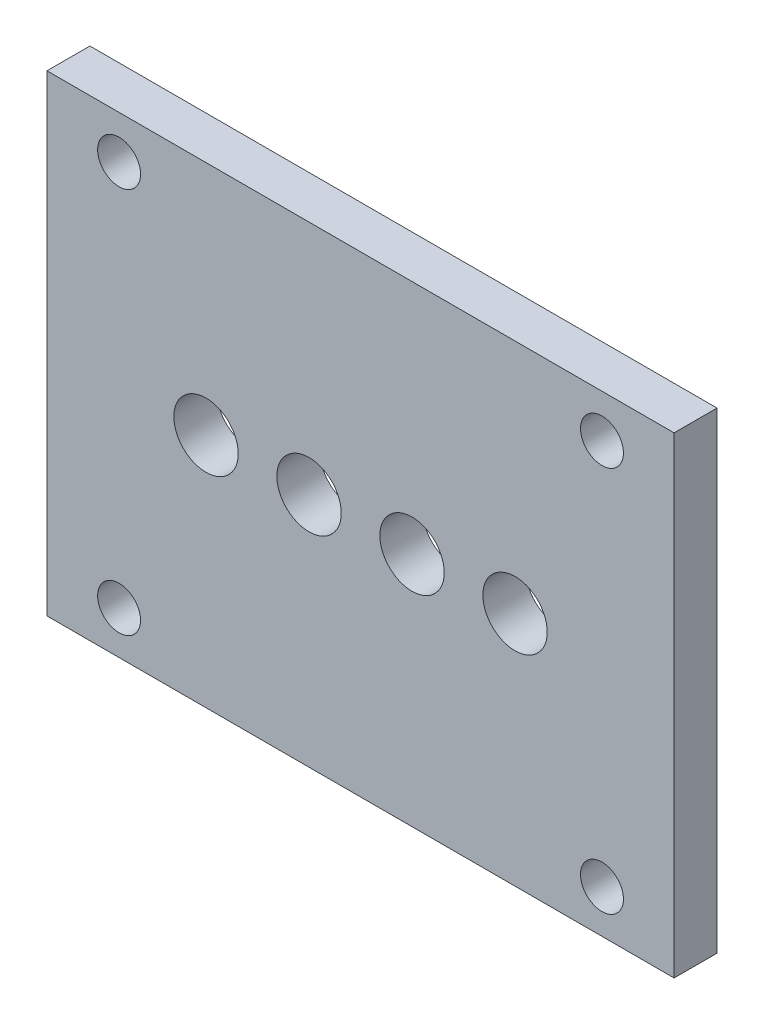
SolidWorks part; units mm, degrees
ref_plane "Front Plane" through (0, 0, 0) normal (0, 0, 1) x (1, 0, 0)
ref_plane "Top Plane" through (0, 0, 0) normal (0, 1, 0) x (1, 0, 0)
ref_plane "Right Plane" through (0, 0, 0) normal (1, 0, 0) x (0, 0, -1)
sketch "Sketch1" plane through (0, 0, 0) normal (0, 0, 1) x (1, 0, 0)
  line L1 (-92.7735, 69.85) -> (92.7735, 69.85)
  line L2 (-92.7735, 69.85) -> (-92.7735, -69.85)
  line L3 (-92.7735, -69.85) -> (92.7735, -69.85)
  line L4 (92.7735, 69.85) -> (92.7735, -69.85)
  dimension "D1" = 139.7
  dimension "D2" = 185.547
  dimension "D3" = 69.85
  dimension "D4" = 92.7735
extrude "Boss-Extrude1" add sketch "Sketch1" along normal blind 12.7
sketch "Sketch2" plane through (0, 0, 12.7) normal (0, 0, 1) x (1, 0, 0)
  line L0 (-45.72, 0) -> (45.72, 0) construction
  circle A0 centre (-45.72, 0) radius 9.525
  circle A1 centre (-15.24, 0) radius 9.525
  circle A2 centre (15.24, 0) radius 9.525
  circle A3 centre (45.72, 0) radius 9.525
  point P3 (0, 0)
  point P9 (0, 0)
  dimension "D2" = 19.05
  dimension "D1" = 4
extrude "Cut-Extrude1" cut sketch "Sketch2" against normal through all
sketch "Sketch3" plane through (0, 0, 12.7) normal (0, 0, 1) x (1, 0, 0)
  line L0 (-71.4375, 57.15) -> (-92.7735, 57.15) construction
  line L1 (92.7735, 69.85) -> (-92.7735, 69.85) construction
  line L2 (-92.7735, -69.85) -> (92.7735, -69.85) construction
  line L3 (-92.7735, 69.85) -> (-92.7735, -69.85) construction
  line L4 (71.4375, 57.15) -> (92.7735, 57.15) construction
  line L5 (-71.4375, -57.15) -> (-92.7735, -57.15) construction
  line L6 (92.7735, -69.85) -> (92.7735, 69.85) construction
  line L7 (71.4375, -57.15) -> (92.7735, -57.15) construction
  circle A0 centre (-71.4375, 57.15) radius 6.35
  circle A1 centre (-71.4375, -57.15) radius 6.35
  circle A2 centre (71.4375, 57.15) radius 6.35
  circle A3 centre (71.4375, -57.15) radius 6.35
  dimension "D1" = 12.7
  dimension "D6" = 12.7
  dimension "D9" = 12.7
  dimension "D12" = 12.7
  dimension "D2" = 142.875
  dimension "D3" = 12.7
  dimension "D4" = 142.875
  dimension "D5" = 12.7
  dimension "D7" = 12.7
  dimension "D10" = 12.7
extrude "Cut-Extrude2" cut sketch "Sketch3" against normal blind 12.7
